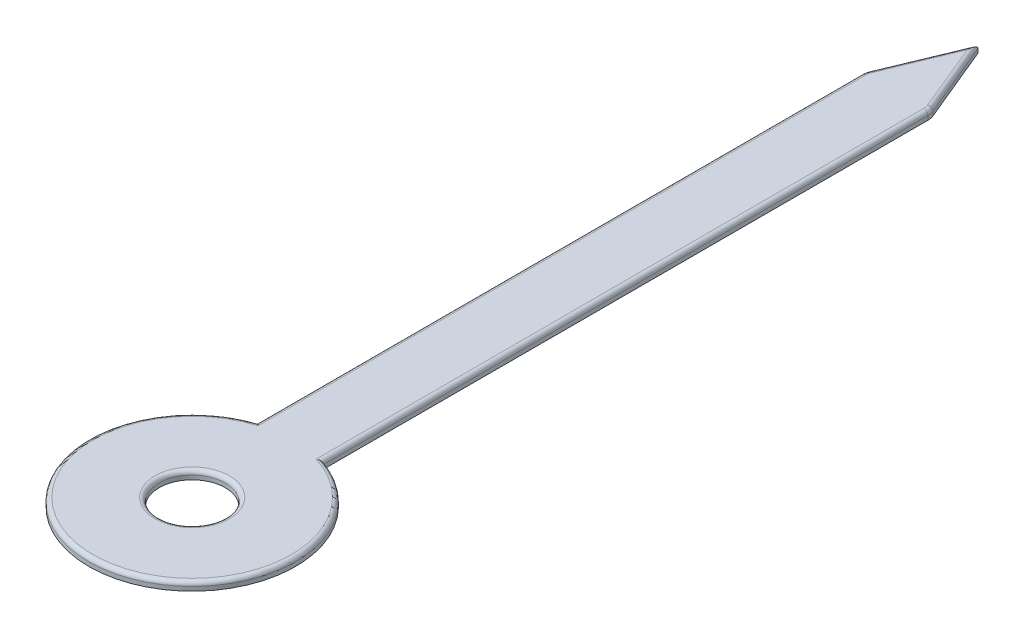
SolidWorks part; units mm, degrees
ref_plane "前视基准面" through (0, 0, 0) normal (0, 0, 1) x (1, 0, 0)
ref_plane "上视基准面" through (0, 0, 0) normal (0, 1, 0) x (1, 0, 0)
ref_plane "右视基准面" through (0, 0, 0) normal (1, 0, 0) x (0, 0, -1)
sketch "草图1" plane through (0, 0, 0) normal (0, 1, 0) x (1, 0, 0)
  line L0 (0, 0) -> (0, 9.5) construction
  line L1 (0.4, 1.1843) -> (0.4, 8.5343)
  line L2 (-0.4, 1.1843) -> (-0.4, 8.5343)
  line L3 (0, 9.5) -> (-0.4, 8.5343)
  line L4 (0, 9.5) -> (0.4, 8.5343)
  line L6 (-0.4, 0) -> (-0.4, 9.5) construction
  arc A0 (-0.4, 1.1843) -> (0.4, 1.1843) centre (0, 0) ccw
  circle A1 centre (0, 0) radius 0.4
  point P4 (0.4, 0)
  point P5 (0.4, 9)
  dimension "D1" = 2.5
  dimension "D3" = 0.8
  dimension "D2" = 9.5
  dimension "D5" = 45
  dimension "D4" = 0.4
extrude "凸台-拉伸2" add sketch "草图1" along normal blind 0.1
fillet "圆角2" radius 0.2 2 edges at (-0.4, 0.05, -8.5343) (0.4, 0.05, -8.5343)
fillet "圆角3" radius 0.05 8 edges at (0, 0.1, 0.4) (0.1924, 0.1, -9.0355) (0.3962, 0.1, -8.5336) (0.4, 0.1, -4.8394) (0, 0.1, 1.25) (-0.4, 0.1, -4.8394) (-0.3962, 0.1, -8.5336) (-0.1924, 0.1, -9.0355)
